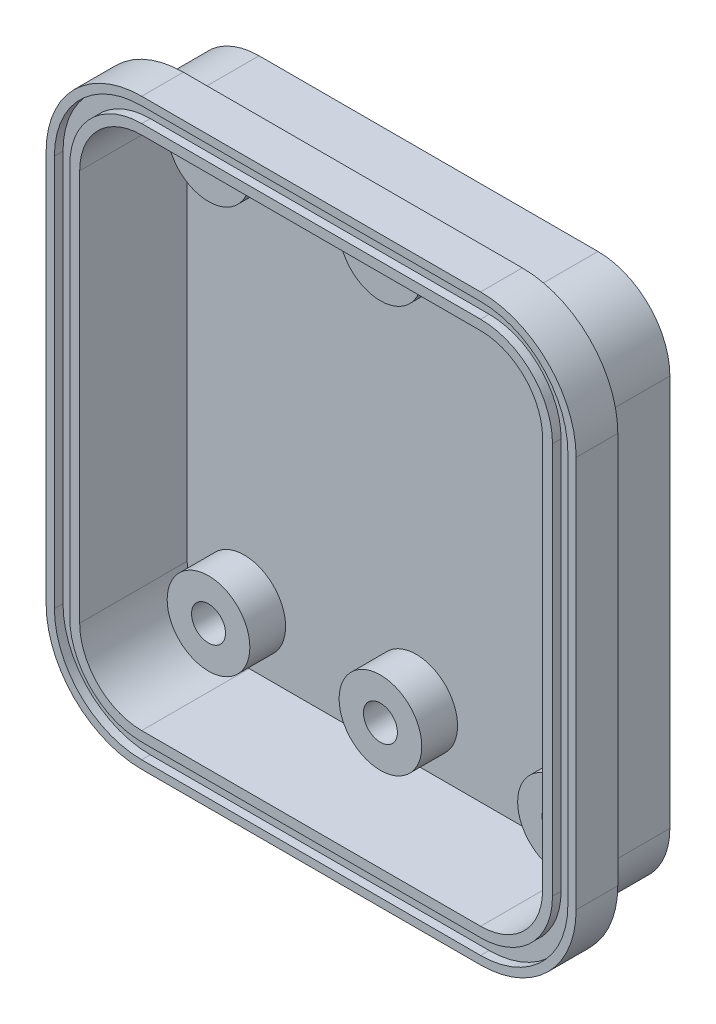
SolidWorks part; units mm, degrees
material "ABS"
ref_plane "X-Y Datum" through (0, 0, 0) normal (0, 0, 1) x (1, 0, 0)
ref_plane "X-Z Datum" through (0, 0, 0) normal (0, 1, 0) x (1, 0, 0)
ref_plane "Y-Z Datum" through (0, 0, 0) normal (1, 0, 0) x (0, 0, -1)
sketch "Sketch1" plane through (0, 0, 0) normal (0, 0, 1) x (1, 0, 0)
  line L0 (26.035, 143.51) -> (78.105, 143.51)
  line L5 (20.066, 67.818) -> (84.074, 67.818) construction
  line L6 (20.066, 67.818) -> (20.066, 139.954) construction
  line L7 (20.066, 139.954) -> (84.074, 139.954) construction
  line L8 (84.074, 67.818) -> (84.074, 139.954) construction
  line L9 (20.066, 67.818) -> (84.074, 139.954) construction
  line L10 (20.066, 139.954) -> (84.074, 67.818) construction
  line L11 (87.63, 73.787) -> (87.63, 133.985)
  line L12 (26.035, 64.262) -> (78.105, 64.262)
  line L13 (16.51, 73.787) -> (16.51, 133.985)
  line L14 (16.51, 143.51) -> (87.63, 143.51) construction
  line L15 (87.63, 64.262) -> (87.63, 143.51) construction
  line L16 (16.51, 64.262) -> (87.63, 64.262) construction
  line L17 (16.51, 64.262) -> (16.51, 143.51) construction
  circle A0 centre (25.292, 135.128) radius 2.1 construction
  circle A1 centre (51.708, 135.128) radius 2.1 construction
  circle A2 centre (79.14, 135.128) radius 2.1 construction
  circle A3 centre (51.708, 72.644) radius 2.1 construction
  circle A4 centre (79.14, 72.644) radius 2.1 construction
  circle A5 centre (25.292, 72.644) radius 2.1 construction
  arc A6 (78.105, 143.51) -> (87.63, 133.985) centre (78.105, 133.985) cw
  arc A7 (87.63, 73.787) -> (78.105, 64.262) centre (78.105, 73.787) cw
  arc A8 (26.035, 64.262) -> (16.51, 73.787) centre (26.035, 73.787) cw
  arc A9 (26.035, 143.51) -> (16.51, 133.985) centre (26.035, 133.985) ccw
  point P18 (52.07, 103.886)
  dimension "D2" = 9.525
  dimension "D1" = 3.556
extrude "Boss-Extrude1" add sketch "Sketch1" along normal blind 16.51 contours L13 A9 L0 A6 L11 A7 L12 A8
shell "Shell1" thickness 1.524
sketch "Sketch2" plane through (0, 0, 0) normal (0, 0, 1) x (1, 0, 0)
  circle A0 centre (25.292, 135.128) radius 6.35
  circle A1 centre (51.708, 135.128) radius 6.35
  circle A3 centre (79.14, 135.128) radius 6.35
  circle A4 centre (25.292, 72.644) radius 6.35
  circle A5 centre (51.708, 72.644) radius 6.35
  circle A6 centre (79.14, 72.644) radius 6.35
  circle A7 centre (25.292, 135.128) radius 2.608
  circle A8 centre (51.708, 135.128) radius 2.608
  circle A9 centre (79.14, 135.128) radius 2.608
  circle A10 centre (25.292, 72.644) radius 2.608
  circle A11 centre (51.708, 72.644) radius 2.608
  circle A12 centre (79.14, 72.644) radius 2.608
extrude "Boss-Extrude2" add sketch "Sketch2" along normal blind 5.5
sketch "Sketch7" plane through (0, 0, 16.51) normal (0, 0, 1) x (1, 0, 0)
  line L17 (78.105, 145.034) -> (26.035, 145.034)
  line L18 (14.986, 133.985) -> (14.986, 73.787)
  line L19 (26.035, 62.738) -> (78.105, 62.738)
  line L20 (89.154, 73.787) -> (89.154, 133.985)
  line L21 (12.6238, 133.985) -> (12.6238, 73.787)
  line L22 (26.035, 60.3758) -> (78.105, 60.3758)
  line L23 (91.5162, 73.787) -> (91.5162, 133.985)
  line L24 (78.105, 147.3962) -> (26.035, 147.3962)
  line L25 (12.6238, 133.985) -> (12.6238, 73.787)
  line L26 (26.035, 60.3758) -> (78.105, 60.3758)
  line L27 (91.5162, 73.787) -> (91.5162, 133.985)
  line L28 (78.105, 147.3962) -> (26.035, 147.3962)
  line L29 (78.105, 148.6662) -> (26.035, 148.6662)
  line L30 (11.3538, 133.985) -> (11.3538, 73.787)
  line L31 (26.035, 59.1058) -> (78.105, 59.1058)
  line L32 (92.7862, 73.787) -> (92.7862, 133.985)
  arc A22 (26.035, 145.034) -> (14.986, 133.985) centre (26.035, 133.985) ccw
  arc A23 (14.986, 73.787) -> (26.035, 62.738) centre (26.035, 73.787) ccw
  arc A24 (78.105, 62.738) -> (89.154, 73.787) centre (78.105, 73.787) ccw
  arc A25 (26.035, 148.6662) -> (11.3538, 133.985) centre (26.035, 133.985) ccw
  arc A26 (12.6238, 73.787) -> (26.035, 60.3758) centre (26.035, 73.787) ccw
  arc A27 (78.105, 60.3758) -> (91.5162, 73.787) centre (78.105, 73.787) ccw
  arc A28 (91.5162, 133.985) -> (78.105, 147.3962) centre (78.105, 133.985) ccw
  arc A29 (26.035, 147.3962) -> (12.6238, 133.985) centre (26.035, 133.985) ccw
  arc A30 (12.6238, 73.787) -> (26.035, 60.3758) centre (26.035, 73.787) ccw
  arc A31 (78.105, 60.3758) -> (91.5162, 73.787) centre (78.105, 73.787) ccw
  arc A32 (91.5162, 133.985) -> (78.105, 147.3962) centre (78.105, 133.985) ccw
  arc A33 (26.035, 147.3962) -> (12.6238, 133.985) centre (26.035, 133.985) ccw
  arc A34 (11.3538, 73.787) -> (26.035, 59.1058) centre (26.035, 73.787) ccw
  arc A35 (78.105, 59.1058) -> (92.7862, 73.787) centre (78.105, 73.787) ccw
  arc A36 (92.7862, 133.985) -> (78.105, 148.6662) centre (78.105, 133.985) ccw
  dimension "D1" = 2.3622
  dimension "D2" = 2.3622
  dimension "D3" = 1.27
extrude "Boss-Extrude9" add sketch "Sketch7" against normal blind 1.3208 separate body contours L32 A36 L29 A25 L30 A34 L31 A35 A33 L28 A32 L27 A31 L26 A30 L25
sketch "Sketch8" plane through (0, 0, 15.1892) normal (0, 0, -1) x (-1, 0, 0)
  line L8 (-11.3538, 73.787) -> (-11.3538, 133.985)
  line L9 (-26.035, 148.6662) -> (-78.105, 148.6662)
  line L10 (-11.3538, 73.787) -> (-11.3538, 133.985)
  line L11 (-26.035, 148.6662) -> (-78.105, 148.6662)
  line L13 (-92.7862, 73.787) -> (-92.7862, 133.985)
  line L14 (-92.7862, 73.787) -> (-92.7862, 133.985)
  line L16 (-26.035, 59.1058) -> (-78.105, 59.1058)
  line L17 (-26.035, 59.1058) -> (-78.105, 59.1058)
  line L20 (-26.035, 145.034) -> (-78.105, 145.034)
  line L21 (-26.035, 145.034) -> (-78.105, 145.034)
  line L33 (-89.154, 133.985) -> (-89.154, 73.787)
  line L34 (-78.105, 62.738) -> (-26.035, 62.738)
  line L35 (-14.986, 73.787) -> (-14.986, 133.985)
  line L36 (-89.154, 133.985) -> (-89.154, 73.787)
  line L37 (-78.105, 62.738) -> (-26.035, 62.738)
  line L38 (-14.986, 73.787) -> (-14.986, 133.985)
  arc A11 (-92.7862, 73.787) -> (-78.105, 59.1058) centre (-78.105, 73.787) ccw
  arc A12 (-26.035, 59.1058) -> (-11.3538, 73.787) centre (-26.035, 73.787) ccw
  arc A13 (-11.3538, 133.985) -> (-26.035, 148.6662) centre (-26.035, 133.985) ccw
  arc A14 (-78.105, 148.6662) -> (-92.7862, 133.985) centre (-78.105, 133.985) ccw
  arc A15 (-26.035, 59.1058) -> (-11.3538, 73.787) centre (-26.035, 73.787) ccw
  arc A16 (-11.3538, 133.985) -> (-26.035, 148.6662) centre (-26.035, 133.985) ccw
  arc A17 (-78.105, 148.6662) -> (-92.7862, 133.985) centre (-78.105, 133.985) ccw
  arc A18 (-92.7862, 73.787) -> (-78.105, 59.1058) centre (-78.105, 73.787) ccw
  arc A24 (-14.986, 133.985) -> (-26.035, 145.034) centre (-26.035, 133.985) ccw
  arc A25 (-78.105, 145.034) -> (-89.154, 133.985) centre (-78.105, 133.985) ccw
  arc A26 (-14.986, 133.985) -> (-26.035, 145.034) centre (-26.035, 133.985) ccw
  arc A27 (-78.105, 145.034) -> (-89.154, 133.985) centre (-78.105, 133.985) ccw
  arc A32 (-78.105, 145.034) -> (-89.154, 133.985) centre (-78.105, 133.985) ccw
  arc A34 (-89.154, 73.787) -> (-78.105, 62.738) centre (-78.105, 73.787) ccw
  arc A35 (-26.035, 62.738) -> (-14.986, 73.787) centre (-26.035, 73.787) ccw
  arc A36 (-89.154, 73.787) -> (-78.105, 62.738) centre (-78.105, 73.787) ccw
  arc A37 (-26.035, 62.738) -> (-14.986, 73.787) centre (-26.035, 73.787) ccw
  arc M17 (-26.035, 147.3962) -> (-12.6238, 133.985) centre (-26.035, 133.985) cw
  line M18 (-12.6238, 133.985) -> (-12.6238, 73.787)
  arc M19 (-12.6238, 73.787) -> (-26.035, 60.3758) centre (-26.035, 73.787) cw
  line M20 (-26.035, 60.3758) -> (-78.105, 60.3758)
  arc M21 (-78.105, 60.3758) -> (-91.5162, 73.787) centre (-78.105, 73.787) cw
  line M22 (-91.5162, 73.787) -> (-91.5162, 133.985)
  arc M23 (-91.5162, 133.985) -> (-78.105, 147.3962) centre (-78.105, 133.985) cw
  line M24 (-78.105, 147.3962) -> (-26.035, 147.3962)
  line M25 (-92.7862, 133.985) -> (-92.7862, 73.787)
  arc M26 (-92.7862, 73.787) -> (-78.105, 59.1058) centre (-78.105, 73.787) ccw
  line M27 (-78.105, 59.1058) -> (-26.035, 59.1058)
  arc M28 (-26.035, 59.1058) -> (-11.3538, 73.787) centre (-26.035, 73.787) ccw
  line M29 (-11.3538, 73.787) -> (-11.3538, 133.985)
  arc M30 (-11.3538, 133.985) -> (-26.035, 148.6662) centre (-26.035, 133.985) ccw
  line M31 (-26.035, 148.6662) -> (-78.105, 148.6662)
  arc M32 (-78.105, 148.6662) -> (-92.7862, 133.985) centre (-78.105, 133.985) ccw
  dimension "D1" = 0
  dimension "D2" = 0
  dimension "D3" = 0
  dimension "D4" = 0
  dimension "D5" = 0
  dimension "D6" = 0
extrude "Boss-Extrude10" add sketch "Sketch8" along normal blind 5.08 contours M32 M25 M26 M27 M28 M29 M30 M31 M24 M17 M18 M19 M20 M21 M22 M23 | A37 L37 A36 L36 A27 L21 A26 L38 M17 M24 M23 M22 M21 M20 M19 M18
sketch "Sketch9" plane through (0, 0, 16.51) normal (0, 0, 1) x (1, 0, 0)
  line L0 (78.105, 148.6662) -> (26.035, 148.6662) construction
  line L1 (11.3538, 103.886) -> (106.4794, 103.886) construction
  line L2 (11.1637, 155.2063) -> (26.035, 155.2063)
  line L3 (52.07, 64.262) -> (52.07, 112.9369) construction
  line L4 (26.035, 155.2063) -> (26.035, 148.6662)
  line L5 (4.8137, 148.8563) -> (4.8137, 133.985)
  line L6 (11.3538, 133.985) -> (4.8137, 133.985)
  line L7 (45.72, 155.0162) -> (45.72, 148.6662)
  line L8 (45.72, 148.6662) -> (58.42, 148.6662)
  line L9 (58.42, 148.6662) -> (58.42, 155.0162)
  line L10 (4.8137, 110.236) -> (11.3538, 110.236)
  line L11 (11.3538, 133.985) -> (11.3538, 73.787) construction
  line L12 (11.3538, 110.236) -> (11.3538, 97.536)
  line L13 (11.3538, 97.536) -> (4.8137, 97.536)
  line L14 (92.7862, 133.985) -> (99.3263, 133.985)
  line L15 (99.3263, 148.8563) -> (99.3263, 133.985)
  line L16 (92.9763, 155.2063) -> (78.105, 155.2063)
  line L17 (78.105, 155.2063) -> (78.105, 148.6662)
  line L18 (78.105, 52.5657) -> (78.105, 59.1058)
  line L19 (92.9763, 52.5657) -> (78.105, 52.5657)
  line L20 (99.3263, 58.9157) -> (99.3263, 73.787)
  line L21 (92.7862, 73.787) -> (99.3263, 73.787)
  line L22 (58.42, 59.1058) -> (58.42, 52.7558)
  line L23 (45.72, 59.1058) -> (58.42, 59.1058)
  line L24 (45.72, 52.7558) -> (45.72, 59.1058)
  line L25 (11.3538, 73.787) -> (4.8137, 73.787)
  line L26 (4.8137, 58.9157) -> (4.8137, 73.787)
  line L27 (11.1637, 52.5657) -> (26.035, 52.5657)
  line L28 (26.035, 52.5657) -> (26.035, 59.1058)
  line L29 (99.3263, 110.236) -> (92.7862, 110.236)
  line L30 (92.7862, 97.536) -> (99.3263, 97.536)
  line L31 (92.7862, 110.236) -> (92.7862, 97.536)
  arc A0 (11.1637, 155.2063) -> (4.8137, 148.8563) centre (11.1637, 148.8563) ccw
  arc A2 (26.035, 148.6662) -> (11.3538, 133.985) centre (26.035, 133.985) ccw construction
  arc A3 (58.42, 155.0162) -> (45.72, 155.0162) centre (52.07, 155.0162) ccw
  arc A8 (4.8137, 110.236) -> (4.8137, 97.536) centre (4.8137, 103.886) ccw
  arc A10 (11.3538, 133.985) -> (26.035, 148.6662) centre (26.035, 133.985) cw
  circle A11 centre (11.1637, 148.8563) radius 2.625
  circle A12 centre (52.07, 155.0162) radius 2.625
  circle A13 centre (4.8137, 103.886) radius 2.625
  circle A14 centre (92.9763, 148.8563) radius 2.625
  arc A15 (92.9763, 155.2063) -> (99.3263, 148.8563) centre (92.9763, 148.8563) cw
  arc A16 (92.7862, 133.985) -> (78.105, 148.6662) centre (78.105, 133.985) ccw
  circle A17 centre (92.9763, 58.9157) radius 2.625
  arc A18 (92.7862, 73.787) -> (78.105, 59.1058) centre (78.105, 73.787) cw
  arc A19 (92.9763, 52.5657) -> (99.3263, 58.9157) centre (92.9763, 58.9157) ccw
  circle A20 centre (52.07, 52.7558) radius 2.625
  arc A21 (58.42, 52.7558) -> (45.72, 52.7558) centre (52.07, 52.7558) cw
  circle A22 centre (11.1637, 58.9157) radius 2.625
  arc A23 (11.1637, 52.5657) -> (4.8137, 58.9157) centre (11.1637, 58.9157) cw
  arc A24 (11.3538, 73.787) -> (26.035, 59.1058) centre (26.035, 73.787) ccw
  circle A25 centre (99.3263, 103.886) radius 2.625
  arc A26 (99.3263, 110.236) -> (99.3263, 97.536) centre (99.3263, 103.886) cw
  point P4 (15.6538, 144.3662)
  point P5 (52.07, 148.6662)
  point P7 (15.6538, 144.3662)
extrude "Boss-Extrude11" [suppressed] add sketch "Sketch9" against normal up to surface (6.4008 mm away)
fillet "Fillet2" [suppressed] radius 2.54
sketch "Sketch10" plane through (0, 0, 16.51) normal (0, 0, 1) x (1, 0, 0)
  line L8 (11.3538, 133.985) -> (11.3538, 73.787)
  line L9 (78.105, 148.6662) -> (26.035, 148.6662)
  line L10 (11.3538, 133.985) -> (11.3538, 73.787)
  line L11 (78.105, 148.6662) -> (26.035, 148.6662)
  line L16 (92.7862, 73.787) -> (92.7862, 133.985)
  line L17 (26.035, 59.1058) -> (78.105, 59.1058)
  line L18 (92.7862, 73.787) -> (92.7862, 133.985)
  line L19 (26.035, 59.1058) -> (78.105, 59.1058)
  arc A6 (11.3538, 73.787) -> (26.035, 59.1058) centre (26.035, 73.787) ccw
  arc A7 (26.035, 148.6662) -> (11.3538, 133.985) centre (26.035, 133.985) ccw
  arc A8 (11.3538, 73.787) -> (26.035, 59.1058) centre (26.035, 73.787) ccw
  arc A9 (26.035, 148.6662) -> (11.3538, 133.985) centre (26.035, 133.985) ccw
  arc A11 (78.105, 59.1058) -> (92.7862, 73.787) centre (78.105, 73.787) ccw
  arc A12 (78.105, 59.1058) -> (92.7862, 73.787) centre (78.105, 73.787) ccw
  circle A13 centre (25.292, 135.128) radius 2.1
  arc A14 (92.7862, 133.985) -> (78.105, 148.6662) centre (78.105, 133.985) ccw
  arc A15 (92.7862, 133.985) -> (78.105, 148.6662) centre (78.105, 133.985) ccw
  circle A16 centre (51.708, 135.128) radius 2.1
  circle A17 centre (79.14, 135.128) radius 2.1
  circle A18 centre (79.14, 72.644) radius 2.1
  circle A19 centre (51.708, 72.644) radius 2.1
  circle A20 centre (25.292, 72.644) radius 2.1
  dimension "D1" = 0
  dimension "D2" = 0
  dimension "D3" = 0
